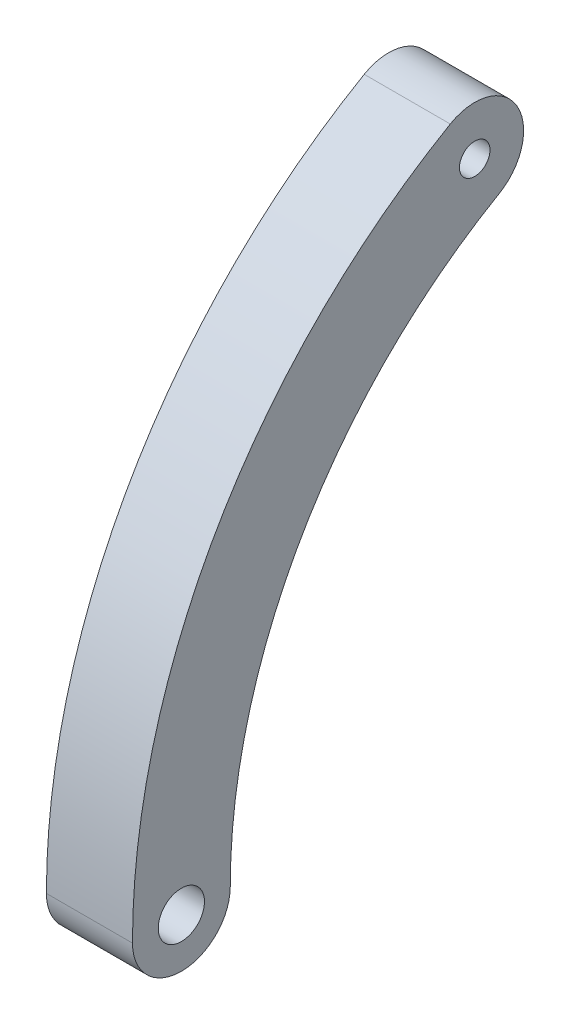
SolidWorks part; units mm, degrees
material "ABS"
ref_plane "Front Plane" through (0, 0, 0) normal (0, 0, 1) x (1, 0, 0)
ref_plane "Top Plane" through (0, 0, 0) normal (0, 1, 0) x (1, 0, 0)
ref_plane "Right Plane" through (0, 0, 0) normal (1, 0, 0) x (0, 0, -1)
sketch "Esquisse1" plane through (0, 0, 0) normal (1, 0, 0) x (0, 0, -1)
  arc A0 (-34.925, 0) -> (-17.4625, 30.2459) centre (0, 0) cw
  arc A1 (-41.275, 0) -> (-20.6375, 35.7452) centre (0, 0) cw
  arc A2 (-41.275, 0) -> (-34.925, 0) centre (-38.1, 0) ccw
  arc A3 (-17.4625, 30.2459) -> (-20.6375, 35.7452) centre (-19.05, 32.9956) ccw
  circle A4 centre (-38.1, 0) radius 1.5
  circle A5 centre (-19.05, 32.9956) radius 0.9922
  dimension "D1" = 3.175
  dimension "D4" = 3
  dimension "D5" = 1.9844
  dimension "D2" = 38.1
  dimension "D3" = 38.1
extrude "Boss.-Extru.1" add sketch "Esquisse1" along normal blind 5.588
